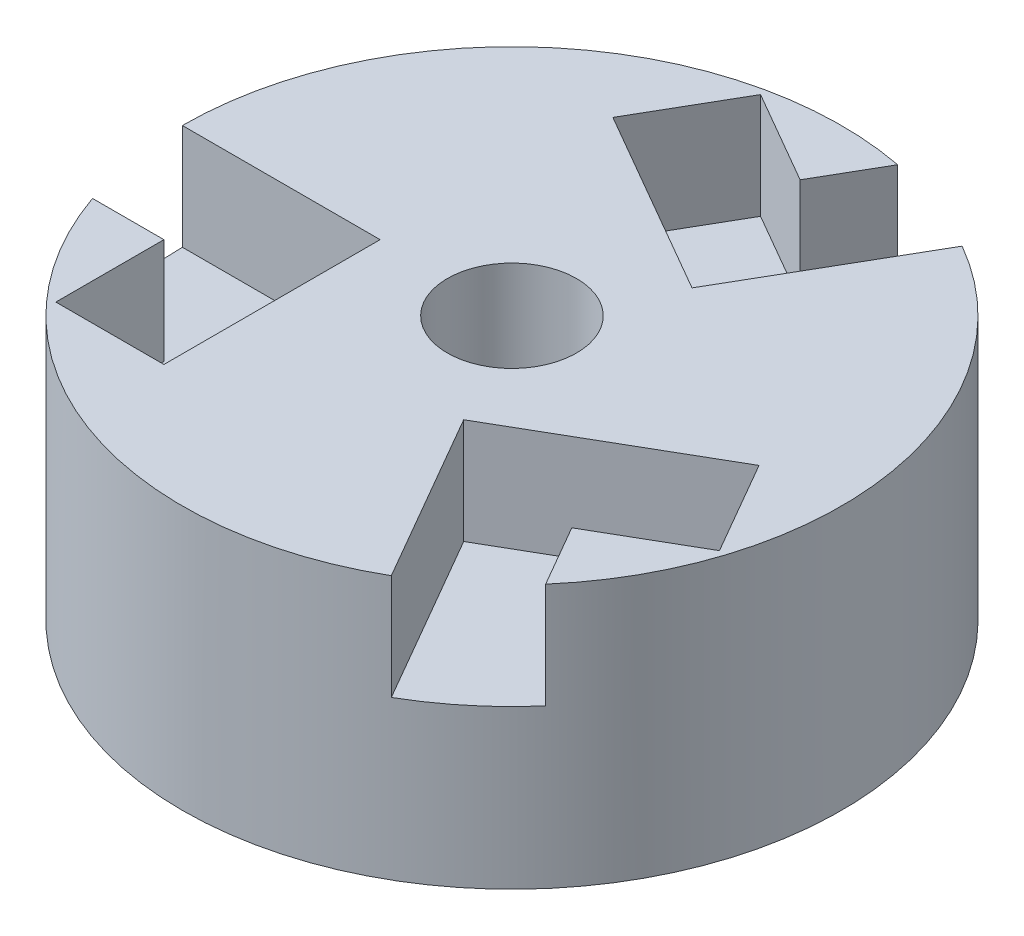
SolidWorks part; units mm, degrees
ref_plane "Front Plane" through (0, 0, 0) normal (0, 0, 1) x (1, 0, 0)
ref_plane "Top Plane" through (0, 0, 0) normal (0, 1, 0) x (1, 0, 0)
ref_plane "Right Plane" through (0, 0, 0) normal (1, 0, 0) x (0, 0, -1)
sketch "Sketch1" plane through (0, 0, 0) normal (0, 1, 0) x (1, 0, 0)
  circle A0 centre (0, 0) radius 25
  dimension "D1" = 50
extrude "Boss-Extrude1" add sketch "Sketch1" along normal blind 20
sketch "Sketch2" plane through (0, 20, 0) normal (0, 1, 0) x (1, 0, 0)
  line L0 (-25, 0) -> (-10, 0)
  line L1 (-10, 0) -> (-10, -16.4)
  line L2 (-10, -16.4) -> (-18.2, -16.4)
  line L3 (-18.2, -16.4) -> (-18.2, -8.2)
  line L4 (-18.2, -8.2) -> (-23.6169, -8.2)
  circle A0 centre (0, 0) radius 25 construction
  arc A1 (-25, 0) -> (-23.6169, -8.2) centre (0, 0) ccw
  dimension "D1" = 8.2
  dimension "D2" = 8.2
  dimension "D3" = 8.2
  dimension "D4" = 10
extrude "Cut-Extrude1" cut sketch "Sketch2" against normal blind 8
pattern_circular "CirPattern1" count 3 over 360 about axis through (0, 0, 0) along (0, 1, 0) of "Cut-Extrude1"
sketch "Sketch7" plane through (0, 0, 0) normal (0, -1, 0) x (1, 0, 0)
  circle A0 centre (0, 0) radius 15.1
  dimension "D1" = 30.2
extrude "Cut-Extrude3" cut sketch "Sketch7" against normal blind 8.7
sketch "Sketch8" plane through (0, 8.7, 0) normal (0, -1, 0) x (1, 0, 0)
  circle A0 centre (0, 0) radius 4.9
  dimension "D1" = 9.8
extrude "Cut-Extrude4" cut sketch "Sketch8" against normal through all
equation "\"D3@Sketch2\"=\"D1@Sketch2\""
equation "\"D2@Sketch2\"=\"D1@Sketch2\""
